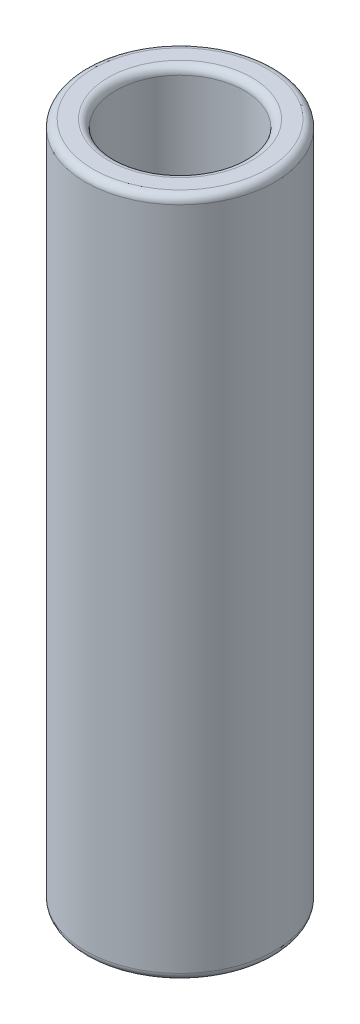
SolidWorks part; units mm, degrees
ref_plane "Front Plane" through (0, 0, 0) normal (0, 0, 1) x (1, 0, 0)
ref_plane "Top Plane" through (0, 0, 0) normal (0, 1, 0) x (1, 0, 0)
ref_plane "Right Plane" through (0, 0, 0) normal (1, 0, 0) x (0, 0, -1)
sketch "Sketch1" plane through (0, 0, 0) normal (0, 1, 0) x (1, 0, 0)
  circle A0 centre (0, 0) radius 2.5
  circle A1 centre (0, 0) radius 1.7
  dimension "D1" = 5
  dimension "D2" = 3.4
extrude "Boss-Extrude1" add sketch "Sketch1" along normal blind 18
fillet "Fillet1" radius 0.2 4 edges at (0, 0, 1.7) (0, 0, 2.5) (0, 18, 1.7) (0, 18, 2.5)
